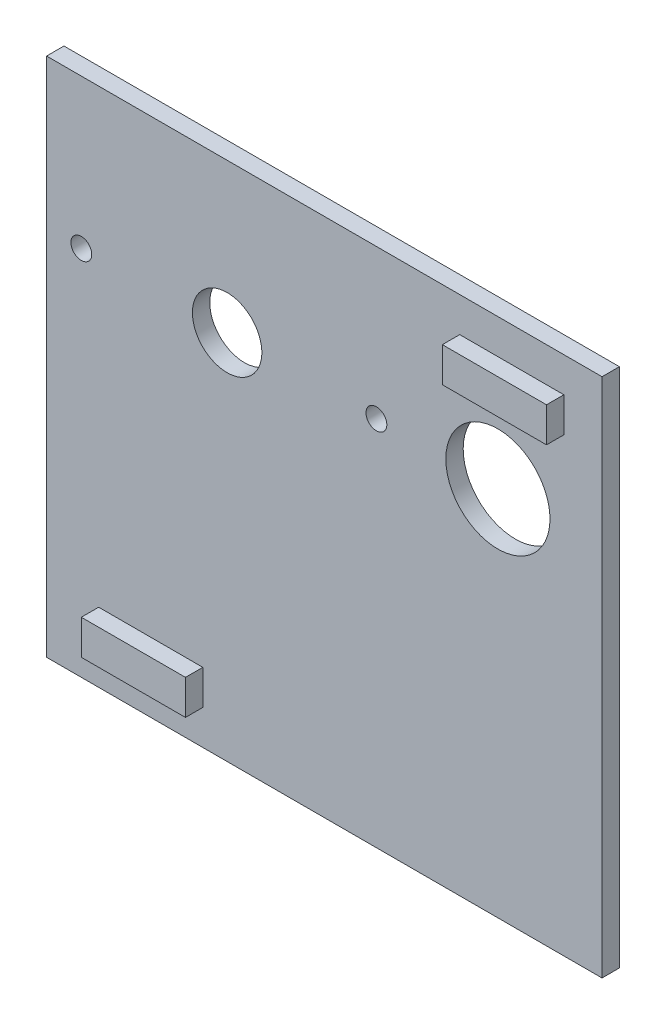
SolidWorks part; units mm, degrees
ref_plane "Front Plane" through (0, 0, 0) normal (0, 0, 1) x (1, 0, 0)
ref_plane "Top Plane" through (0, 0, 0) normal (0, 1, 0) x (1, 0, 0)
ref_plane "Right Plane" through (0, 0, 0) normal (1, 0, 0) x (0, 0, -1)
sketch "Sketch1" plane through (0, 0, 0) normal (0, 0, 1) x (1, 0, 0)
  line L1 (0, 0) -> (-160, 0)
  line L2 (0, 0) -> (0, -150)
  line L3 (0, -150) -> (-160, -150)
  line L4 (-160, 0) -> (-160, -150)
  dimension "D1" = 160
  dimension "D2" = 150
extrude "Boss-Extrude1" add sketch "Sketch1" along normal blind 5
sketch "Sketch2" plane through (0, 0, 5) normal (0, 0, 1) x (1, 0, 0)
  line L0 (-160, -150) -> (0, -150) construction
  line L1 (-41, -10) -> (-11, -10)
  line L2 (-41, -10) -> (-41, -20)
  line L3 (-41, -20) -> (-11, -20)
  line L4 (-11, -10) -> (-11, -20)
  line L7 (0, 0) -> (-160, 0) construction
  line L8 (-160, 0) -> (-160, -150) construction
  line L9 (0, -150) -> (0, 0) construction
  line L12 (-145, -130) -> (-115, -130)
  line L13 (-145, -130) -> (-145, -140)
  line L14 (-145, -140) -> (-115, -140)
  line L15 (-115, -130) -> (-115, -140)
  dimension "D1" = 30
  dimension "D2" = 11
  dimension "D3" = 10
  dimension "D4" = 10
  dimension "D5" = 15
  dimension "D6" = 30
  dimension "D7" = 10
  dimension "D8" = 10
extrude "Boss-Extrude2" add sketch "Sketch2" along normal blind 5
sketch "Sketch4" plane through (0, 0, 10) normal (0, 0, 1) x (1, 0, 0)
  line L0 (0, 0) -> (-160, 0) construction
  line L1 (0, 0) -> (-160, 0) construction
  line L2 (-160, 0) -> (-160, -150) construction
  line L3 (0, -150) -> (0, 0) construction
  circle A0 centre (-150, -43) radius 3
  circle A1 centre (-108, -43) radius 10
  circle A2 centre (-65, -43) radius 3
  circle A3 centre (-30, -43) radius 15
  dimension "D1" = 6
  dimension "D2" = 20
  dimension "D3" = 6
  dimension "D4" = 43
  dimension "D5" = 43
  dimension "D6" = 43
  dimension "D7" = 10
  dimension "D8" = 52
  dimension "D9" = 95
  dimension "D10" = 30
  dimension "D11" = 30
  dimension "D12" = 43
extrude "Cut-Extrude1" cut sketch "Sketch4" against normal blind 15
